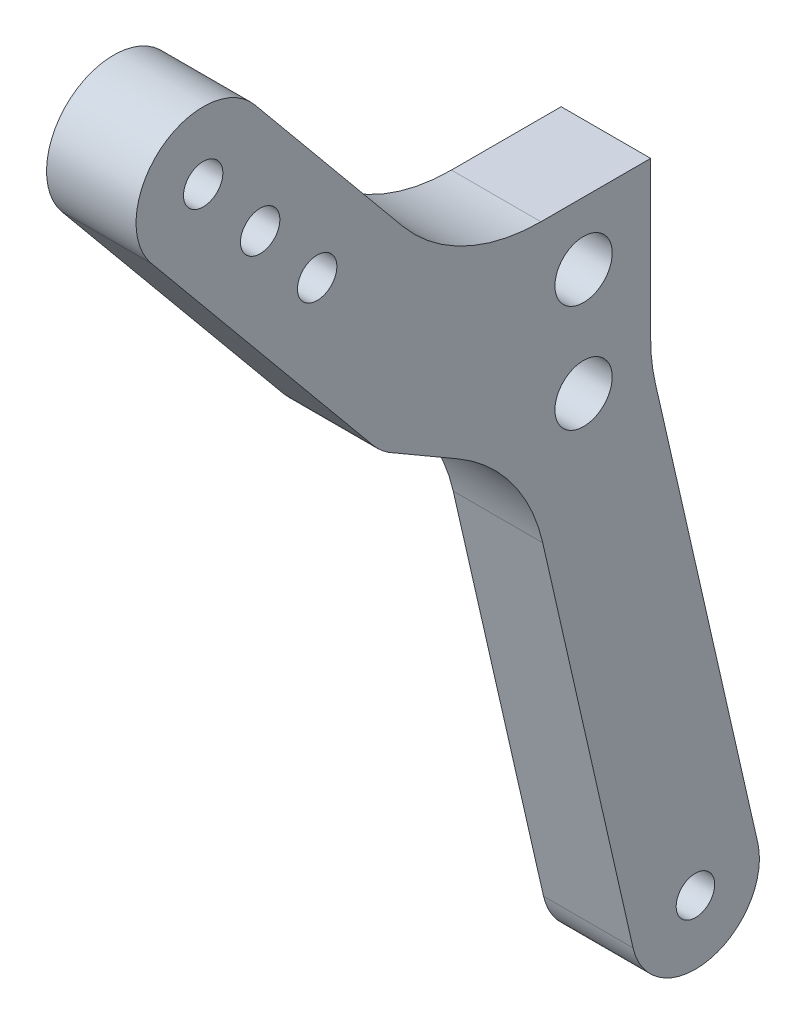
SolidWorks part; units mm, degrees
ref_plane "Front Plane" through (0, 0, 0) normal (0, 0, 1) x (1, 0, 0)
ref_plane "Top Plane" through (0, 0, 0) normal (0, 1, 0) x (1, 0, 0)
ref_plane "Right Plane" through (0, 0, 0) normal (1, 0, 0) x (0, 0, -1)
sketch "Sketch1" plane through (0, 0, 0) normal (0, 0, 1) x (1, 0, 0)
  line L1 (-2.5, -3.75) -> (2.5, -3.75)
  line L2 (-2.5, -3.75) -> (-2.5, 3.75)
  line L3 (-2.5, 3.75) -> (2.5, 3.75)
  line L4 (2.5, -3.75) -> (2.5, 3.75)
  line L5 (-2.5, -3.75) -> (2.5, 3.75) construction
  line L6 (-2.5, 3.75) -> (2.5, -3.75) construction
  point P0 (0, 0)
  dimension "D1" = 5
  dimension "D2" = 7.5
extrude "Boss-Extrude1" add sketch "Sketch1" along normal blind 13
sketch "Sketch6" plane through (2.5, 0, 0) normal (1, 0, 0) x (0, 0, -1)
  line L0 (-12.6104, 0) -> (-25, 15) construction
  line L1 (-15.5017, -2.3881) -> (-27.8913, 12.6119)
  line L2 (-9.7192, 2.3881) -> (-22.1087, 17.3881)
  line L3 (0, 0) -> (-13, 0) construction
  line L4 (0, -3.75) -> (0, 3.75) construction
  line L5 (-13, -3.75) -> (-13, 3.75) construction
  arc A0 (-15.5017, -2.3881) -> (-9.7192, 2.3881) centre (-12.6104, 0) ccw
  arc A1 (-22.1087, 17.3881) -> (-27.8913, 12.6119) centre (-25, 15) ccw
  point P3 (-18.8052, 7.5)
  dimension "D1" = 15
  dimension "D2" = 12
  dimension "D3" = 7.5
extrude "Boss-Extrude4" add sketch "Sketch6" against normal up to surface (5 mm away) contours L1 A1 L2 A0 up to face at (-2.5, 0, 6.5)
sketch "Sketch2" plane through (2.5, 0, 0) normal (1, 0, 0) x (0, 0, -1)
  circle A0 centre (-25, 15) radius 1.1
  arc A1 (-22.1087, 17.3881) -> (-27.8913, 12.6119) centre (-25, 15) ccw construction
  dimension "D1" = 2.2
extrude "Cut-Extrude1" cut sketch "Sketch2" against normal through all
fillet "Fillet1" [suppressed] radius 3.75
pattern_linear "LPattern1" count 3 spacing 5 along (0, -0.771, -0.6368) of "Cut-Extrude1"
sketch "Sketch3" plane through (2.5, 0, 0) normal (1, 0, 0) x (0, 0, -1)
  line L0 (-10.8441, 3.75) -> (0, 3.75) construction
  line L2 (0, -8.75) -> (-7.5, -8.75) construction
  circle A0 centre (-3.75, 0.25) radius 1.6
  point P8 (-3.75, -8.75)
  dimension "D1" = 3.2
  dimension "D2" = 3.5
extrude "Cut-Extrude2" cut sketch "Sketch3" against normal through all
sketch "Sketch4" plane through (2.5, 0, 0) normal (1, 0, 0) x (0, 0, -1)
  line L0 (0, -3.75) -> (0, -8.75)
  line L1 (0, -8.75) -> (-5, -8.75)
  line L2 (-5, -8.75) -> (-14.3827, -3.3048)
  line L4 (-14.3827, -3.3048) -> (0, -3.75)
  arc A0 (-15.5017, -2.3881) -> (-13, -3.7297) centre (-12.6104, 0) ccw construction
  dimension "D2" = 5
  dimension "D3" = 5
extrude "Boss-Extrude2" add sketch "Sketch4" against normal up to surface (5 mm away) contours L0 L1 L2 L4 up to face at (-2.5, 0.25, 2.15)
pattern_linear "LPattern2" count 2 spacing 6 along (0, -1, 0) of "Cut-Extrude2"
sketch "Sketch5" plane through (2.5, 0, 0) normal (1, 0, 0) x (0, 0, -1)
  line L0 (-38.1016, -33.1601) -> (2.5, -33.1601) construction
  line L1 (2.5, -44) -> (2.5, -33.1601) construction
  line L2 (2.5, -33.1601) -> (-3.75, -5.75) construction
  line L3 (-0.9855, -33.9549) -> (-7.2355, -6.5448)
  line L4 (5.9855, -32.3654) -> (-0.2645, -4.9552)
  arc A0 (-0.9855, -33.9549) -> (5.9855, -32.3654) centre (2.5, -33.1601) ccw
  arc A1 (-0.2645, -4.9552) -> (-7.2355, -6.5448) centre (-3.75, -5.75) ccw
  circle A2 centre (2.5, -33.1601) radius 1.075
  circle A3 centre (-3.75, -5.75) radius 1.6 construction
  circle A4 centre (-3.75, -5.75) radius 1.6
  circle A5 centre (-38.1016, -33.1601) radius 1.1 construction
  point P1 (-0.625, -19.4551)
  dimension "D1" = 2.15
  dimension "D2" = 2.5
extrude "Boss-Extrude3" add sketch "Sketch5" against normal up to surface (5 mm away) up to face at (-2.5, -5.75, 2.15)
fillet "Fillet2" radius 10 3 edges at (0, -7.5911, 6.997) (0, -6.1151, 0) (0, 3.75, 10.8441)
